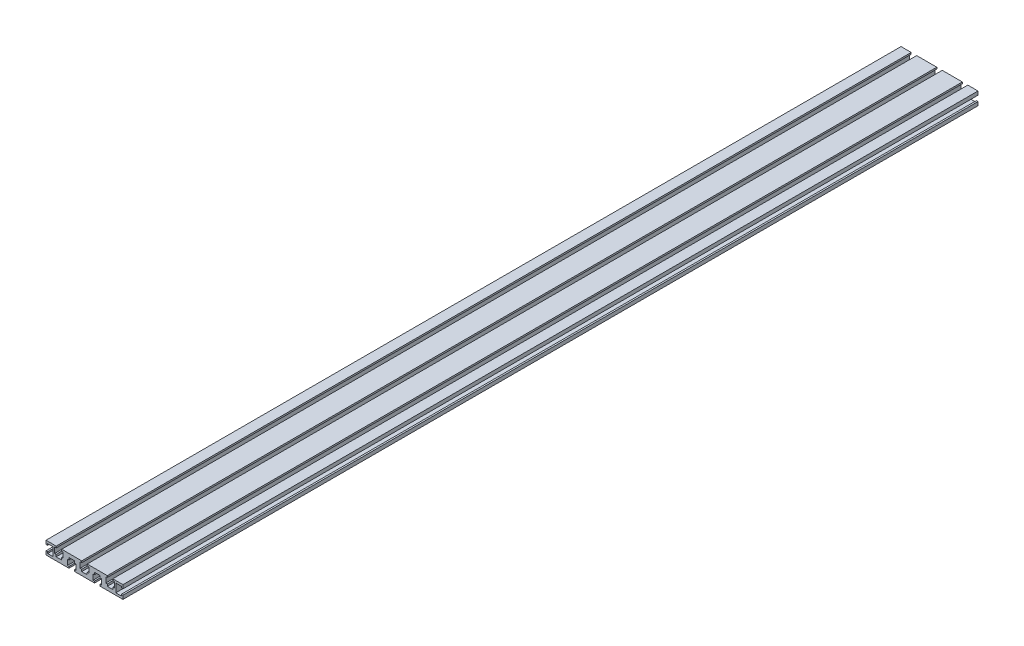
SolidWorks part; units mm, degrees
ref_plane "前视基准面" through (0, 0, 0) normal (0, 0, 1) x (1, 0, 0)
ref_plane "上视基准面" through (0, 0, 0) normal (0, 1, 0) x (1, 0, 0)
ref_plane "右视基准面" through (0, 0, 0) normal (1, 0, 0) x (0, 0, -1)
sketch "草图1" plane through (0, 0, 0) normal (0, 0, 1) x (1, 0, 0)
  line L0 (-20.13, 1.0514) -> (-18.33, 1.0514)
  line L1 (-18.33, 1.0514) -> (-18.33, 3.5514)
  line L2 (-18.33, 3.5514) -> (-11.93, 3.5514)
  line L3 (-11.93, 3.5514) -> (-11.93, 1.0514)
  line L4 (-11.93, 1.0514) -> (-10.13, 1.0514)
  line L5 (-10.13, 1.0514) -> (-10.13, -5.4486)
  line L6 (-10.13, -5.4486) -> (-11.93, -5.4486)
  line L7 (-11.93, -5.4486) -> (-11.93, -7.3486)
  line L8 (-11.93, -7.3486) -> (11.57, -7.3486)
  line L9 (11.57, -7.3486) -> (11.57, -5.4486)
  line L10 (11.57, -5.4486) -> (9.77, -5.4486)
  line L11 (9.77, -5.4486) -> (9.77, 1.0514)
  line L12 (9.77, 1.0514) -> (11.57, 1.0514)
  line L13 (11.57, 1.0514) -> (11.57, 3.5514)
  line L14 (11.57, 3.5514) -> (17.97, 3.5514)
  line L15 (17.97, 3.5514) -> (17.97, 1.0514)
  line L16 (17.97, 1.0514) -> (19.77, 1.0514)
  line L17 (19.77, 1.0514) -> (19.77, -5.4486)
  line L18 (19.77, -5.4486) -> (17.97, -5.4486)
  line L19 (17.97, -5.4486) -> (17.97, -7.3486)
  line L20 (17.97, -7.3486) -> (44.82, -7.3486)
  line L21 (44.82, -7.3486) -> (44.82, -3.0486)
  line L22 (44.82, -3.0486) -> (42.92, -3.0486)
  line L23 (42.92, -3.0486) -> (42.92, -4.8486)
  line L24 (42.92, -4.8486) -> (36.42, -4.8486)
  line L25 (36.42, -4.8486) -> (36.42, 5.1514)
  line L26 (36.42, 5.1514) -> (42.92, 5.1514)
  line L27 (42.92, 5.1514) -> (42.92, 3.3514)
  line L28 (42.92, 3.3514) -> (44.82, 3.3514)
  line L29 (44.82, 3.3514) -> (44.82, 7.6514)
  line L30 (44.82, 7.6514) -> (32.92, 7.6514)
  line L31 (32.92, 7.6514) -> (32.92, 5.7514)
  line L32 (32.92, 5.7514) -> (34.72, 5.7514)
  line L33 (34.72, 5.7514) -> (34.72, -0.7486)
  line L34 (34.72, -0.7486) -> (32.92, -0.7486)
  line L35 (32.92, -0.7486) -> (32.92, -3.2486)
  line L36 (32.92, -3.2486) -> (26.52, -3.2486)
  line L37 (26.52, -3.2486) -> (26.52, -0.7486)
  line L38 (26.52, -0.7486) -> (24.72, -0.7486)
  line L39 (24.72, -0.7486) -> (24.72, 5.7514)
  line L40 (24.72, 5.7514) -> (26.52, 5.7514)
  line L41 (26.52, 5.7514) -> (26.52, 7.6514)
  line L42 (26.52, 7.6514) -> (3.02, 7.6514)
  line L43 (3.02, 7.6514) -> (3.02, 5.7514)
  line L44 (3.02, 5.7514) -> (4.82, 5.7514)
  line L45 (4.82, 5.7514) -> (4.82, -0.7486)
  line L46 (4.82, -0.7486) -> (3.02, -0.7486)
  line L47 (3.02, -0.7486) -> (3.02, -3.2486)
  line L48 (3.02, -3.2486) -> (-3.38, -3.2486)
  line L49 (-3.38, -3.2486) -> (-3.38, -0.7486)
  line L50 (-3.38, -0.7486) -> (-5.18, -0.7486)
  line L51 (-5.18, -0.7486) -> (-5.18, 5.7514)
  line L52 (-5.18, 5.7514) -> (-3.38, 5.7514)
  line L53 (-3.38, 5.7514) -> (-3.38, 7.6514)
  line L54 (-3.38, 7.6514) -> (-26.88, 7.6514)
  line L55 (-26.88, 7.6514) -> (-26.88, 5.7514)
  line L56 (-26.88, 5.7514) -> (-25.08, 5.7514)
  line L57 (-25.08, 5.7514) -> (-25.08, -0.7486)
  line L58 (-25.08, -0.7486) -> (-26.88, -0.7486)
  line L59 (-26.88, -0.7486) -> (-26.88, -3.2486)
  line L60 (-26.88, -3.2486) -> (-33.28, -3.2486)
  line L61 (-33.28, -3.2486) -> (-33.28, -0.7486)
  line L62 (-33.28, -0.7486) -> (-35.08, -0.7486)
  line L63 (-35.08, -0.7486) -> (-35.08, 5.7514)
  line L64 (-35.08, 5.7514) -> (-33.28, 5.7514)
  line L65 (-33.28, 5.7514) -> (-33.28, 7.6514)
  line L66 (-33.28, 7.6514) -> (-45.18, 7.6514)
  line L67 (-45.18, 7.6514) -> (-45.18, 3.3514)
  line L68 (-45.18, 3.3514) -> (-43.28, 3.3514)
  line L69 (-43.28, 3.3514) -> (-43.28, 5.1514)
  line L70 (-43.28, 5.1514) -> (-36.78, 5.1514)
  line L71 (-36.78, 5.1514) -> (-36.78, -4.8486)
  line L72 (-36.78, -4.8486) -> (-43.28, -4.8486)
  line L73 (-43.28, -4.8486) -> (-43.28, -3.0486)
  line L74 (-43.28, -3.0486) -> (-45.18, -3.0486)
  line L75 (-45.18, -3.0486) -> (-45.18, -7.3486)
  line L76 (-45.18, -7.3486) -> (-18.33, -7.3486)
  line L77 (-18.33, -7.3486) -> (-18.33, -5.4486)
  line L78 (-18.33, -5.4486) -> (-20.13, -5.4486)
  line L79 (-20.13, -5.4486) -> (-20.13, 1.0514)
extrude "凸台-拉伸1" add sketch "草图1" along normal blind 1000
